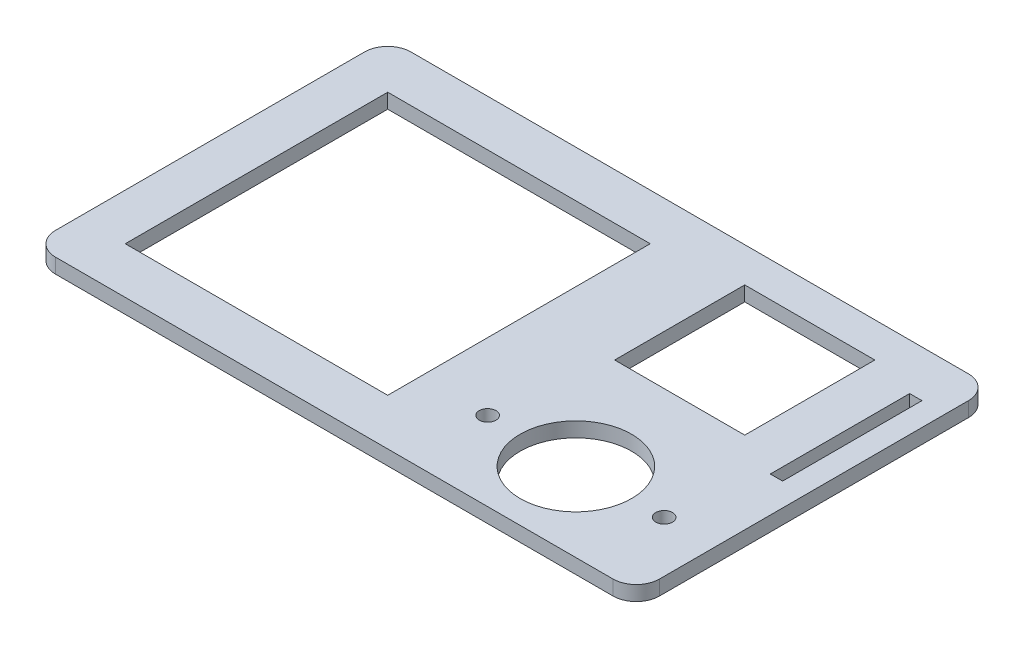
SolidWorks part; units mm, degrees
ref_plane "Front Plane" through (0, 0, 0) normal (0, 0, 1) x (1, 0, 0)
ref_plane "Top Plane" through (0, 0, 0) normal (0, 1, 0) x (1, 0, 0)
ref_plane "Right Plane" through (0, 0, 0) normal (1, 0, 0) x (0, 0, -1)
sketch "Sketch1" plane through (0, 0, 0) normal (0, 1, 0) x (1, 0, 0)
  line L0 (119, 17) -> (100, 17) construction
  line L1 (0, 0) -> (130, 0)
  line L2 (0, 0) -> (0, 76.5)
  line L3 (0, 76.5) -> (130, 76.5)
  line L4 (130, 0) -> (130, 76.5)
  line L5 (10, 66.5) -> (66.5, 66.5)
  line L6 (10, 66.5) -> (10, 10)
  line L7 (10, 10) -> (66.5, 10)
  line L8 (66.5, 66.5) -> (66.5, 10)
  line L9 (84.35, 69) -> (112.35, 69)
  line L10 (84.35, 69) -> (84.35, 41)
  line L11 (84.35, 41) -> (112.35, 41)
  line L12 (112.35, 69) -> (112.35, 41)
  line L13 (100, 0) -> (100, 76.5) construction
  line L15 (125, 66.5) -> (122.35, 66.5)
  line L16 (125, 66.5) -> (125, 36.5)
  line L17 (125, 36.5) -> (122.35, 36.5)
  line L18 (122.35, 66.5) -> (122.35, 36.5)
  circle A0 centre (100, 17) radius 12
  circle A1 centre (119, 17) radius 1.8
  circle A2 centre (81, 17) radius 1.8
  dimension "D4" = 24
  dimension "D5" = 3.6
  dimension "D10" = 17
  dimension "D1" = 19
  dimension "D2" = 56.5
  dimension "D3" = 28
  dimension "D6" = 10
  dimension "D7" = 10
  dimension "D8" = 10
  dimension "D9" = 130
  dimension "D11" = 30
  dimension "D12" = 33.5
  dimension "D13" = 7.5
  dimension "D14" = 2.65
  dimension "D15" = 10
  dimension "D16" = 30
  dimension "D17" = 10
  dimension "D18" = 5
extrude "Boss-Extrude1" add sketch "Sketch1" along normal blind 3.175
fillet "Fillet1" radius 5 4 edges at (0, 1.5875, -76.5) (0, 1.5875, 0) (130, 1.5875, -76.5) (130, 1.5875, 0)
